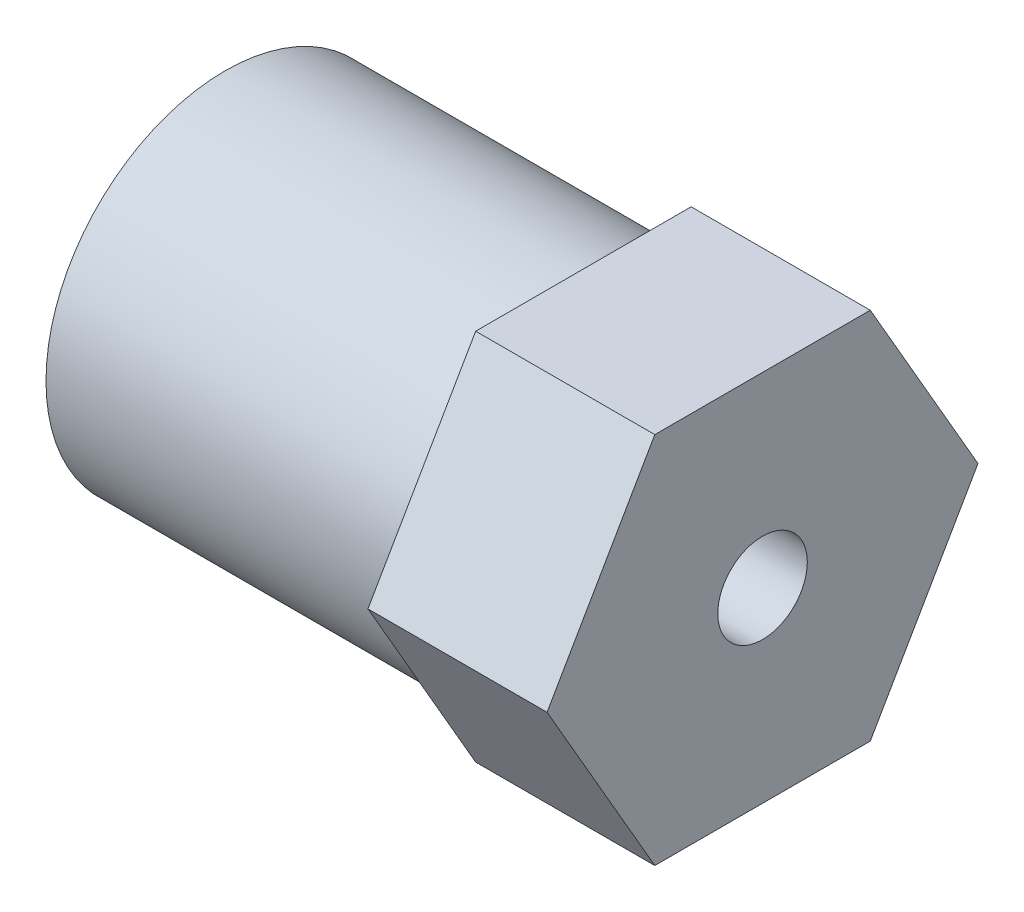
SolidWorks part; units mm, degrees
ref_plane "Front Plane" through (0, 0, 0) normal (0, 0, 1) x (1, 0, 0)
ref_plane "Top Plane" through (0, 0, 0) normal (0, 1, 0) x (1, 0, 0)
ref_plane "Right Plane" through (0, 0, 0) normal (1, 0, 0) x (0, 0, -1)
sketch "Sketch1" plane through (0, 0, 0) normal (1, 0, 0) x (0, 0, -1)
  line L1 (7.2169, 0) -> (3.6084, 6.25)
  line L2 (3.6084, 6.25) -> (-3.6084, 6.25)
  line L3 (-3.6084, 6.25) -> (-7.2169, 0)
  line L4 (-7.2169, 0) -> (-3.6084, -6.25)
  line L5 (-3.6084, -6.25) -> (3.6084, -6.25)
  line L6 (3.6084, -6.25) -> (7.2169, 0)
  circle A0 centre (0, 0) radius 6.25 construction
  dimension "D1" = 12.5
extrude "Boss-Extrude1" add sketch "Sketch1" along normal blind 6
sketch "Sketch2" plane through (0, 0, 0) normal (-1, 0, 0) x (0, 0, 1)
  circle A0 centre (0, 0) radius 6
  dimension "D1" = 12
extrude "Boss-Extrude2" add sketch "Sketch2" along normal blind 12
sketch "Sketch3" plane through (-12, 0, 0) normal (-1, 0, 0) x (0, 0, 1)
  circle A0 centre (0, 0) radius 3
  dimension "D1" = 6
extrude "Cut-Extrude1" cut sketch "Sketch3" against normal blind 12
sketch "Sketch4" plane through (6, 0, 0) normal (1, 0, 0) x (0, 0, -1)
  circle A0 centre (0, 0) radius 1.5
  dimension "D1" = 3
extrude "Cut-Extrude2" cut sketch "Sketch4" against normal through all
